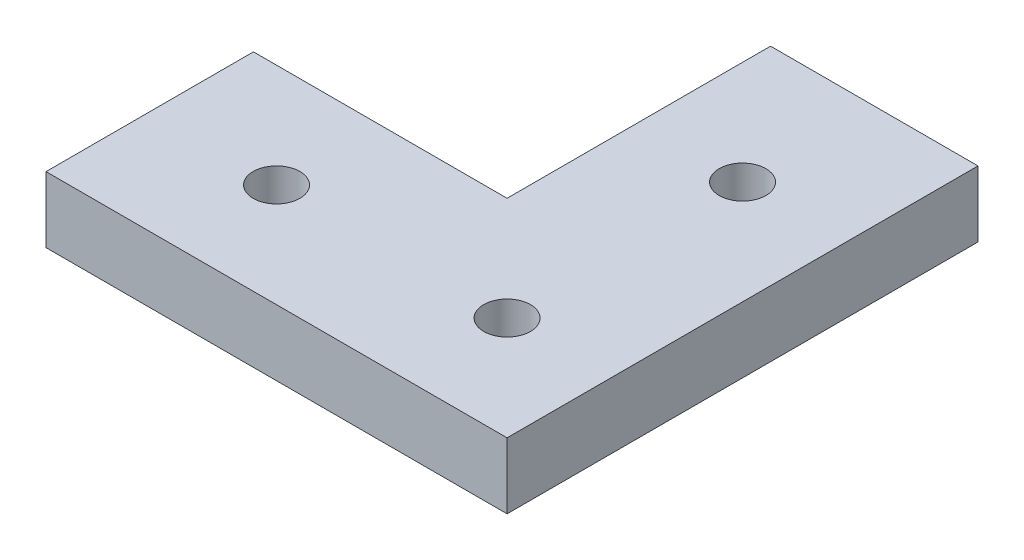
SolidWorks part; units mm, degrees
ref_plane "Front Plane" through (0, 0, 0) normal (0, 0, 1) x (1, 0, 0)
ref_plane "Top Plane" through (0, 0, 0) normal (0, 1, 0) x (1, 0, 0)
ref_plane "Right Plane" through (0, 0, 0) normal (1, 0, 0) x (0, 0, -1)
sketch "Sketch1" plane through (0, 0, 0) normal (0, 1, 0) x (1, 0, 0)
  line L1 (0, 0) -> (44.45, 0)
  line L2 (0, 0) -> (0, 20)
  line L3 (0, 20) -> (44.45, 20)
  line L4 (44.45, 0) -> (44.45, 20)
  line L5 (44.45, 20) -> (24.45, 20)
  line L6 (44.45, 20) -> (44.45, 45.4)
  line L7 (44.45, 45.4) -> (24.45, 45.4)
  line L8 (24.45, 20) -> (24.45, 45.4)
  dimension "D1" = 44.45
  dimension "D2" = 20
  dimension "D3" = 20
  dimension "D4" = 25.4
extrude "Boss-Extrude1" add sketch "Sketch1" along normal blind 6.35 contours L8 L3 L6 L7 | L1 L4 L3 L2
sketch "Sketch2" plane through (0, 6.35, 0) normal (0, 1, 0) x (1, 0, 0)
  circle A0 centre (12.225, 10) radius 2.25
  circle A1 centre (34.45, 10) radius 2.25
  circle A2 centre (34.45, 32.7) radius 2.25
  dimension "D1" = 4.5
  dimension "D2" = 4.5
  dimension "D3" = 4.5
extrude "Cut-Extrude1" cut sketch "Sketch2" against normal blind 6.35
